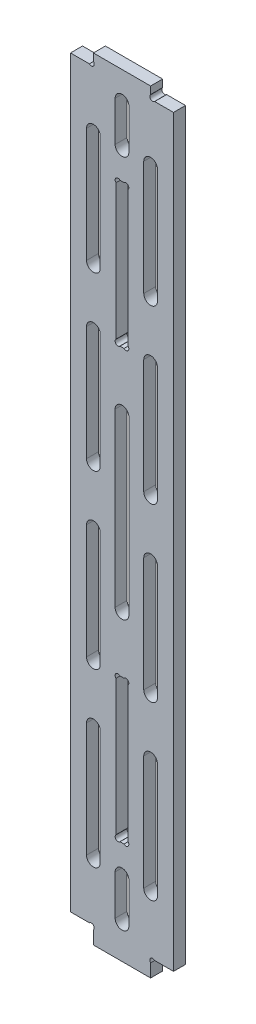
SolidWorks part; units mm, degrees
material "自定义塑料碳纤维-1.6"
ref_plane "前视基准面" through (0, 0, 0) normal (0, 0, 1) x (1, 0, 0)
ref_plane "上视基准面" through (0, 0, 0) normal (0, 1, 0) x (1, 0, 0)
ref_plane "右视基准面" through (0, 0, 0) normal (1, 0, 0) x (0, 0, -1)
other "Configuration Table"
sketch "草图1" plane through (0, 0, 0) normal (0, 0, 1) x (1, 0, 0)
  line L0 (-5, 65) -> (-5, 67)
  line L1 (-9, 65) -> (9, 65)
  line L2 (-9, 65) -> (-9, -65)
  line L3 (-9, -65) -> (9, -65)
  line L4 (9, 65) -> (9, -65)
  line L5 (0, -65) -> (0, 65) construction
  line L6 (-9, 0) -> (9, 0) construction
  line L7 (-5, 67) -> (5, 67)
  line L8 (5, 67) -> (5, 65)
  line L9 (0, 65) -> (0, 67)
  line L10 (-5, -65) -> (-5, -68)
  line L11 (-5, -68) -> (5, -68)
  line L12 (5, -68) -> (5, -65)
  line L13 (0, -65) -> (0, -68)
  point P0 (0, 0)
  dimension "D1" = 130
  dimension "D2" = 18
  dimension "D3" = 10
  dimension "D4" = 2
  dimension "D5" = 10
  dimension "D6" = 3
extrude "凸台-拉伸1" add sketch "草图1" along normal mid plane 2.1 contours L4 L1 L2 L3 | L1 L9 L7 L0 | L9 L1 L8 L7 | L3 L13 L11 L12 | L13 L3 L10 L11
sketch "草图5" plane through (0, 0, 1.05) normal (0, 0, 1) x (1, 0, 0)
  line L0 (5.7071, -65) -> (5, -65.7071) construction
  line L1 (-5, -65.7071) -> (-5.7071, -65) construction
  line L2 (-5, -65) -> (-5, -68) construction
  line L3 (-5.3536, -65.3536) -> (-5, -65)
  line L4 (5.3536, -65.3536) -> (5, -65)
  line L5 (5.7071, 65) -> (5, 65.7071) construction
  line L6 (5, 67) -> (5, 65) construction
  line L7 (5.3536, 65.3536) -> (5, 65)
  line L8 (5, 65) -> (9, 65) construction
  line L9 (-5, 65.7071) -> (-5.7071, 65) construction
  line L10 (-5, 65) -> (-5, 67) construction
  line L11 (-5.3536, 65.3536) -> (-5, 65)
  line L12 (5, -65) -> (9, -65) construction
  circle A0 centre (5.3536, 65.3536) radius 0.5
  circle A1 centre (-5.3536, 65.3536) radius 0.5
  circle A2 centre (5.3536, -65.3536) radius 0.5
  circle A3 centre (-5.3536, -65.3536) radius 0.5
  dimension "D1" = 1
extrude "切除-拉伸3" cut sketch "草图5" against normal through all
sketch "草图2" plane through (0, 0, 1.05) normal (0, 0, 1) x (1, 0, 0)
  line L0 (0, -68) -> (0, 67)
  line L1 (-5, -68) -> (5, -68) construction
  line L2 (-5, 67) -> (5, 67) construction
  line L4 (-1.05, 50.05) -> (1.05, 50.05)
  line L5 (-1.05, 50.05) -> (-1.05, 24.95)
  line L6 (-1.05, 24.95) -> (1.05, 24.95)
  line L7 (1.05, 50.05) -> (1.05, 24.95)
  line L8 (0, 24.95) -> (0, 50.05) construction
  line L9 (-1.05, 37.5) -> (1.05, 37.5) construction
  line L10 (-1.05, -50.05) -> (1.05, -50.05)
  line L11 (-1.05, -50.05) -> (-1.05, -24.95)
  line L12 (-1.05, -24.95) -> (1.05, -24.95)
  line L13 (1.05, -50.05) -> (1.05, -24.95)
  line L14 (0, -24.95) -> (0, -50.05) construction
  line L15 (-1.05, -37.5) -> (1.05, -37.5) construction
  point P6 (0, 37.5)
  point P10 (0, -37.5)
  dimension "D1" = 24.95
  dimension "D2" = 25.1
  dimension "D3" = 2.1
  dimension "D4" = 24.95
  dimension "D5" = 25.1
  dimension "D6" = 2.1
extrude "切除-拉伸1" cut sketch "草图2" against normal blind 10 contours L7 L4 L0 L6 | L5 L6 L0 L4 | L10 L13 L12 L0 | L12 L11 L10 L0
sketch "草图6" plane through (0, 0, 1.05) normal (0, 0, 1) x (1, 0, 0)
  line L0 (0.6964, 25.3036) -> (1.05, 24.95)
  line L1 (-0.6964, 25.3036) -> (-1.05, 24.95)
  line L2 (0.6964, 49.6964) -> (1.05, 50.05)
  line L3 (-0.6964, 49.6964) -> (-1.05, 50.05)
  line L4 (-1.05, 50.05) -> (1.05, 50.05) construction
  line L5 (-1.05, 24.95) -> (1.05, 24.95) construction
  circle A0 centre (0.6964, 49.6964) radius 0.5
  circle A1 centre (-0.6964, 49.6964) radius 0.5
  circle A2 centre (0.6964, 25.3036) radius 0.5
  circle A3 centre (-0.6964, 25.3036) radius 0.5
  dimension "D5" = 1
  dimension "D1" = 45
  dimension "D2" = 45
  dimension "D3" = 45
  dimension "D4" = 45
extrude "切除-拉伸4" cut sketch "草图6" against normal through all
mirror "镜向1" about plane through (0, 0, 0) normal (0, 1, 0) of "切除-拉伸4"
sketch "草图4" plane through (0, 0, 1.05) normal (0, 0, 1) x (1, 0, 0)
  line L1 (5, 65) -> (5, 55) construction
  line L2 (5, 67) -> (5, 65.7071) construction
  line L5 (5.7071, 65) -> (9, 65) construction
  line L6 (5, 55) -> (5, 35)
  line L7 (5, 35) -> (5, 25) construction
  line L8 (5, 25) -> (5, 5)
  line L9 (5, 5) -> (5, -5) construction
  line L10 (5, -5) -> (5, -25)
  line L11 (5, -25) -> (5, -35) construction
  line L12 (5, -35) -> (5, -55)
  line L13 (5, 55) -> (5, 35) construction
  line L15 (6.2, 55) -> (6.2, 35)
  line L16 (3.8, 55) -> (3.8, 35)
  line L17 (5, 25) -> (5, 5) construction
  line L18 (6.2, 25) -> (6.2, 5)
  line L19 (3.8, 25) -> (3.8, 5)
  line L20 (5, -5) -> (5, -25) construction
  line L21 (6.2, -5) -> (6.2, -25)
  line L22 (3.8, -5) -> (3.8, -25)
  line L23 (5, -55) -> (5, -35) construction
  line L24 (3.8, -55) -> (3.8, -35)
  line L25 (6.2, -55) -> (6.2, -35)
  arc A0 (6.2, 55) -> (3.8, 55) centre (5, 55) ccw
  arc A1 (3.8, 35) -> (6.2, 35) centre (5, 35) ccw
  arc A2 (6.2, 25) -> (3.8, 25) centre (5, 25) ccw
  arc A3 (3.8, 5) -> (6.2, 5) centre (5, 5) ccw
  arc A4 (6.2, -5) -> (3.8, -5) centre (5, -5) ccw
  arc A5 (3.8, -25) -> (6.2, -25) centre (5, -25) ccw
  arc A6 (3.8, -55) -> (6.2, -55) centre (5, -55) ccw
  arc A7 (6.2, -35) -> (3.8, -35) centre (5, -35) ccw
  point P0 (5, 45)
  point P18 (5, 15)
  point P23 (5, -15)
  point P28 (5, -45)
  dimension "D9" = 1.2
  dimension "D1" = 10
  dimension "D2" = 20
  dimension "D3" = 10
  dimension "D4" = 20
  dimension "D5" = 10
  dimension "D6" = 20
  dimension "D7" = 10
  dimension "D8" = 20
extrude "切除-拉伸5" cut sketch "草图4" against normal through all
mirror "镜向2" about plane through (0, 0, 0) normal (1, 0, 0) of "切除-拉伸5"
sketch "草图7" plane through (0, 0, 1.05) normal (0, 0, 1) x (1, 0, 0)
  line L0 (0, 62.05) -> (0, 55.05) construction
  line L2 (0, -1.155) -> (0, 1.155) construction
  line L3 (1.2, 62.05) -> (1.2, 55.05)
  line L4 (-1.2, 62.05) -> (-1.2, 55.05)
  line L5 (0, 15) -> (0, -15) construction
  line L6 (1.2, 15) -> (1.2, -15)
  line L7 (-1.2, 15) -> (-1.2, -15)
  line L8 (0, -55.05) -> (0, -62.05) construction
  line L9 (1.2, -55.05) -> (1.2, -62.05)
  line L10 (-1.2, -55.05) -> (-1.2, -62.05)
  line L11 (-0.3429, -50.05) -> (0.3429, -50.05) construction
  line L12 (-0.3429, 50.05) -> (0.3429, 50.05) construction
  arc A0 (1.2, 62.05) -> (-1.2, 62.05) centre (0, 62.05) ccw
  arc A1 (-1.2, 55.05) -> (1.2, 55.05) centre (0, 55.05) ccw
  arc A2 (1.2, 15) -> (-1.2, 15) centre (0, 15) ccw
  arc A3 (-1.2, -15) -> (1.2, -15) centre (0, -15) ccw
  arc A4 (1.2, -55.05) -> (-1.2, -55.05) centre (0, -55.05) ccw
  arc A5 (-1.2, -62.05) -> (1.2, -62.05) centre (0, -62.05) ccw
  point P5 (0, 58.55)
  point P11 (0, 0)
  point P18 (0, -58.55)
  dimension "D6" = 1.2
  dimension "D1" = 5
  dimension "D2" = 5
  dimension "D3" = 7
  dimension "D4" = 7
  dimension "D5" = 30
extrude "切除-拉伸6" cut sketch "草图7" against normal through all
sketch "草图8" plane through (0, 0, 1.05) normal (0, 0, 1) x (1, 0, 0)
  line L0 (5, -68) -> (10, -68)
  line L1 (10, -68) -> (10, -71)
  line L2 (10, -71) -> (-10, -71)
  line L3 (-10, -71) -> (-10, -68)
  line L4 (-10, -68) -> (-5, -68)
  line L5 (5, -68) -> (-5, -68)
  line L6 (5, 67) -> (10, 67)
  line L7 (10, 67) -> (10, 70)
  line L8 (10, 70) -> (-10, 70)
  line L9 (-10, 70) -> (-10, 67)
  line L10 (-10, 67) -> (-5, 67)
  line L11 (-5, 67) -> (5, 67)
  dimension "D1" = 5
  dimension "D2" = 5
  dimension "D3" = 3
  dimension "D4" = 5
  dimension "D5" = 5
  dimension "D6" = 3
extrude "凸台-拉伸2" [suppressed] add sketch "草图8" against normal up to surface (2.1 mm away)
sketch "草图9" [suppressed] plane through (0, 0, -1.05) normal (0, 0, -1) x (-1, 0, 0)
  line L0 (-5, -67.2929) -> (-5.7071, -68)
  line L1 (-5, -68) -> (-5, -65.7071) construction
  line L2 (5, -67.2929) -> (5.7071, -68)
  line L3 (5, -65.7071) -> (5, -68) construction
  line L4 (10, -68) -> (5, -68) construction
  line L5 (5.3536, -67.6464) -> (5, -68)
  line L6 (-5, -68) -> (-5.3536, -67.6464)
  line L7 (5, 66.2929) -> (5.7071, 67)
  line L8 (5.3536, 66.6464) -> (5, 67)
  line L9 (-5, 66.2929) -> (-5.7071, 67)
  line L10 (-5.3536, 66.6464) -> (-5, 67)
  line L16 (5.7071, -65) -> (9, -65)
  line L17 (9, -65) -> (9, 65)
  line L18 (9, 65) -> (5.7071, 65)
  line L19 (5, 65.7071) -> (5, 67)
  line L20 (5, 67) -> (10, 67)
  line L21 (-5, 67) -> (-5, 65.7071)
  line L22 (-5.7071, 65) -> (-9, 65)
  line L23 (-9, 65) -> (-9, -65)
  line L24 (-9, -65) -> (-5.7071, -65)
  line L25 (-5, -65.7071) -> (-5, -68)
  line L26 (-5, -68) -> (-10, -68)
  line L27 (-10, -68) -> (-10, -71)
  line L28 (-10, -71) -> (10, -71)
  line L29 (10, -71) -> (10, -68)
  line L30 (10, -68) -> (5, -68)
  line L31 (5, -68) -> (5, -65.7071)
  line L32 (5.7071, -65) -> (9, -65)
  line L33 (9, -65) -> (9, 65)
  line L34 (9, 65) -> (5.7071, 65)
  line L35 (5, 65.7071) -> (5, 67)
  line L37 (-5, 67) -> (-5, 65.7071)
  line L38 (-5.7071, 65) -> (-9, 65)
  line L39 (-9, 65) -> (-9, -65)
  line L40 (-9, -65) -> (-5.7071, -65)
  line L41 (-5, -65.7071) -> (-5, -68)
  line L42 (-5, -68) -> (-10, -68)
  line L43 (-10, -68) -> (-10, -71)
  line L44 (-10, -71) -> (10, -71)
  line L45 (10, -71) -> (10, -68)
  line L46 (10, -68) -> (5, -68)
  line L47 (5, -68) -> (5, -65.7071)
  line L59 (5, 67) -> (10, 67)
  line L60 (10, 67) -> (10, 70)
  line L61 (10, 67) -> (10, 70)
  line L62 (10, 70) -> (-10, 70)
  line L63 (10, 70) -> (-10, 70)
  line L64 (-10, 70) -> (-10, 67)
  line L65 (-10, 70) -> (-10, 67)
  line L66 (-10, 67) -> (-5, 67)
  line L67 (-10, 67) -> (-5, 67)
  circle A0 centre (5.3536, -67.6464) radius 0.5
  circle A1 centre (-5.3536, -67.6464) radius 0.5
  circle A2 centre (5.3536, 66.6464) radius 0.5
  circle A3 centre (-5.3536, 66.6464) radius 0.5
  arc A5 (5.7071, -65) -> (5, -65.7071) centre (5.3536, -65.3536) ccw
  arc A6 (5, 65.7071) -> (5.7071, 65) centre (5.3536, 65.3536) ccw
  arc A7 (-5.7071, 65) -> (-5, 65.7071) centre (-5.3536, 65.3536) ccw
  arc A8 (-5, -65.7071) -> (-5.7071, -65) centre (-5.3536, -65.3536) ccw
  arc A9 (5.7071, -65) -> (5, -65.7071) centre (5.3536, -65.3536) ccw
  arc A10 (5, 65.7071) -> (5.7071, 65) centre (5.3536, 65.3536) ccw
  arc A11 (-5.7071, 65) -> (-5, 65.7071) centre (-5.3536, 65.3536) ccw
  arc A12 (-5, -65.7071) -> (-5.7071, -65) centre (-5.3536, -65.3536) ccw
  dimension "D2" = 1
  dimension "D1" = 0
extrude "切除-拉伸7" [suppressed] cut sketch "草图9" against normal through all contours L41 A1 | L42 A1 | L47 A0 | L46 A0 | L59 A2 | L35 A2 | L37 A3 | L67 A3
fillet "圆角1" [suppressed] radius 0.2
fillet "圆角2" [suppressed] radius 2
fillet "圆角3" [suppressed] radius 0.2
